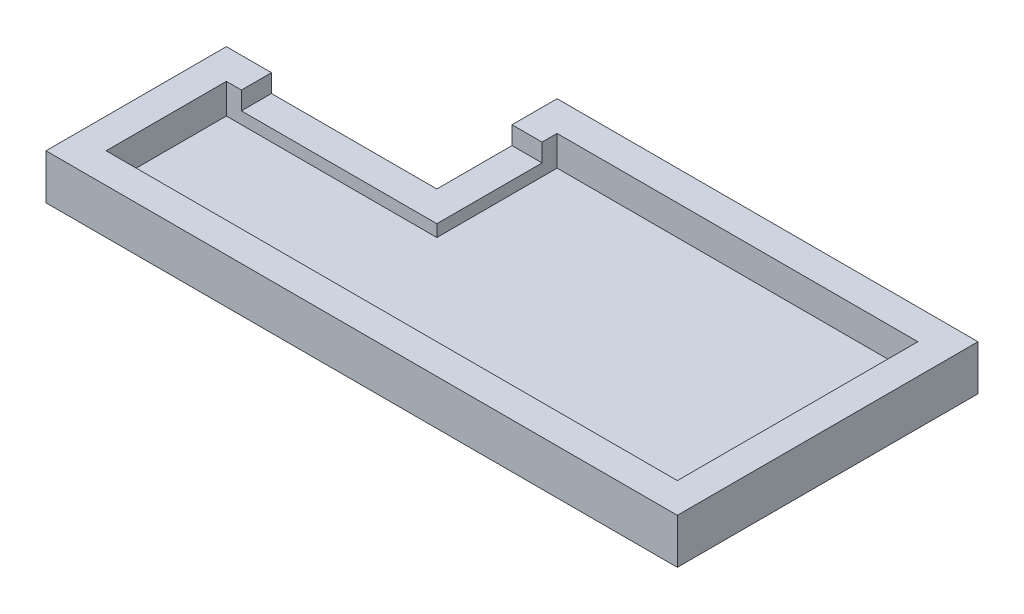
SolidWorks part; units mm, degrees
ref_plane "Front Plane" through (0, 0, 0) normal (0, 0, 1) x (1, 0, 0)
ref_plane "Top Plane" through (0, 0, 0) normal (0, 1, 0) x (1, 0, 0)
ref_plane "Right Plane" through (0, 0, 0) normal (1, 0, 0) x (0, 0, -1)
sketch "Sketch1" plane through (0, 0, 0) normal (0, 1, 0) x (1, 0, 0)
  line L0 (0, 0) -> (0, 76.2)
  line L3 (0, 76.2) -> (88.9, 76.2)
  line L4 (88.9, 76.2) -> (88.9, 127)
  line L5 (88.9, 127) -> (266.7, 127)
  line L6 (266.7, 127) -> (266.7, 0)
  line L7 (266.7, 0) -> (0, 0)
  dimension "D2" = 266.7
  dimension "D3" = 177.8
  dimension "D4" = 88.9
  dimension "D6" = 50.8
  dimension "D7" = 127
extrude "Boss-Extrude1" add sketch "Sketch1" along normal blind 19.05
sketch "Sketch2" plane through (0, 19.05, 0) normal (0, 1, 0) x (1, 0, 0)
  line L0 (12.7, 63.5) -> (101.6, 63.5)
  line L1 (101.6, 63.5) -> (101.6, 114.3)
  line L2 (101.6, 114.3) -> (254, 114.3)
  line L3 (254, 114.3) -> (254, 12.7)
  line L4 (254, 12.7) -> (12.7, 12.7)
  line L5 (12.7, 12.7) -> (12.7, 63.5)
  line L7 (0, 0) -> (266.7, 0) construction
  line L8 (266.7, 0) -> (266.7, 127) construction
  line L9 (266.7, 127) -> (88.9, 127) construction
  line L10 (88.9, 127) -> (88.9, 76.2) construction
  line L11 (88.9, 76.2) -> (0, 76.2) construction
  line L12 (0, 76.2) -> (0, 0) construction
  dimension "D1" = 12.7
  dimension "D2" = 12.7
  dimension "D3" = 12.7
  dimension "D4" = 12.7
  dimension "D5" = 12.7
  dimension "D6" = 12.7
extrude "Cut-Extrude1" cut sketch "Sketch2" against normal blind 12.7
sketch "Sketch3" plane through (0, 19.05, 0) normal (0, 1, 0) x (1, 0, 0)
  line L0 (19.05, 76.2) -> (19.05, 63.5)
  line L1 (88.9, 76.2) -> (0, 76.2) construction
  line L2 (101.6, 63.5) -> (12.7, 63.5) construction
  line L3 (19.05, 63.5) -> (101.6, 63.5)
  line L4 (101.6, 63.5) -> (101.6, 107.95)
  line L5 (101.6, 114.3) -> (101.6, 63.5) construction
  line L6 (101.6, 107.95) -> (88.9, 107.95)
  line L7 (88.9, 127) -> (88.9, 76.2) construction
  line L8 (88.9, 107.95) -> (88.9, 76.2)
  line L9 (88.9, 76.2) -> (19.05, 76.2)
  line L10 (12.7, 63.5) -> (12.7, 12.7) construction
  line L11 (254, 114.3) -> (101.6, 114.3) construction
  dimension "D1" = 6.35
  dimension "D2" = 6.35
extrude "Cut-Extrude2" cut sketch "Sketch3" against normal blind 7.62
